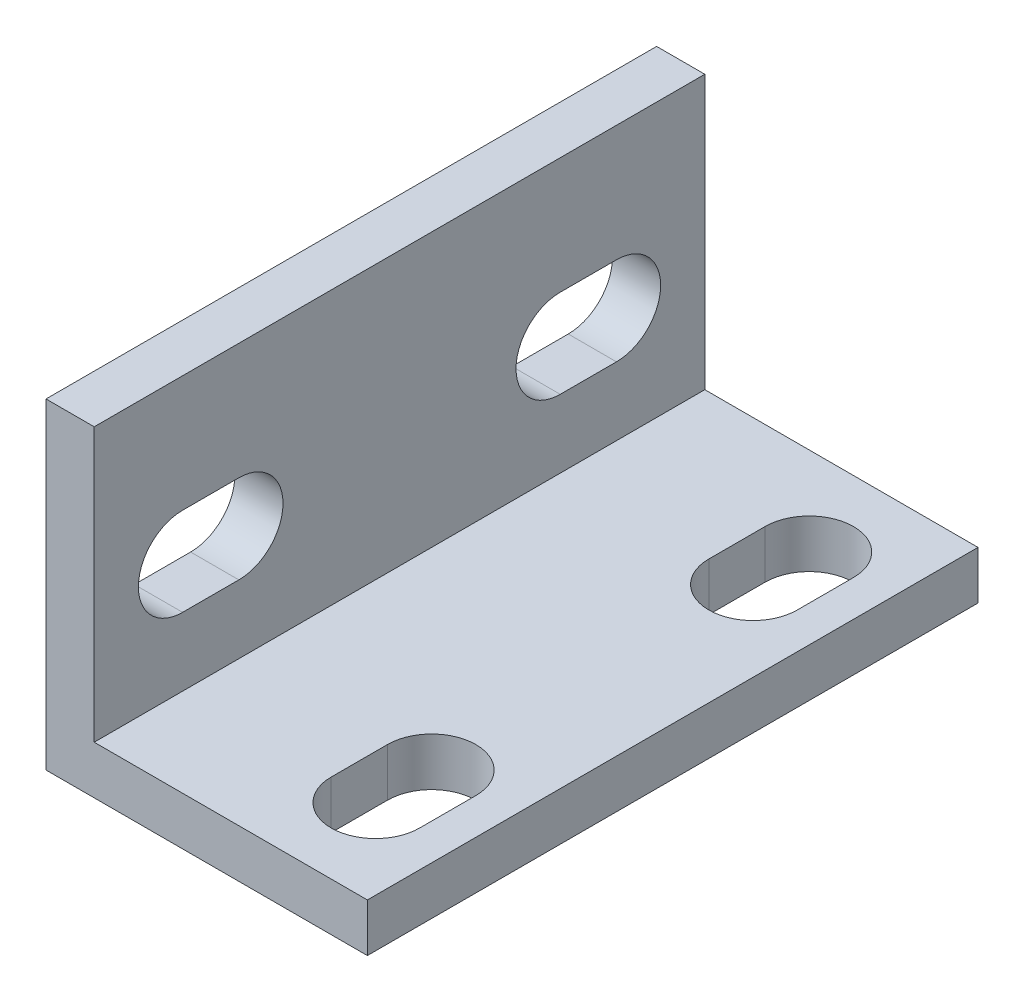
SolidWorks part; units mm, degrees
material "6061-T6 (SS)"
ref_plane "Front Plane" through (0, 0, 0) normal (0, 0, 1) x (1, 0, 0)
ref_plane "Top Plane" through (0, 0, 0) normal (0, 1, 0) x (1, 0, 0)
ref_plane "Right Plane" through (0, 0, 0) normal (1, 0, 0) x (0, 0, -1)
sketch "Sketch1" plane through (0, 0, 0) normal (0, 0, 1) x (1, 0, 0)
  line L0 (0, 20) -> (0, 0)
  line L1 (0, 0) -> (20, 0)
  dimension "D1" = 20
extrude "Extrude-Thin1" add sketch "Sketch1" along normal blind 38 thin thin type one direction reverse wall 3
sketch "Sketch2" plane through (3, 0, 0) normal (1, 0, 0) x (0, 0, -1)
  line L0 (-19, 20) -> (-19, 3) construction
  line L1 (-38, 20) -> (0, 20) construction
  line L2 (-38, 3) -> (0, 3) construction
  line L3 (-29, 10) -> (-32.5, 10) construction
  line L4 (-29, 7.25) -> (-32.5, 7.25)
  line L5 (-29, 12.75) -> (-32.5, 12.75)
  line L6 (-9, 10) -> (-5.5, 10) construction
  line L7 (-9, 7.25) -> (-5.5, 7.25)
  line L8 (-38, 3) -> (0, 3) construction
  line L9 (-9, 12.75) -> (-5.5, 12.75)
  arc A0 (-29, 7.25) -> (-29, 12.75) centre (-29, 10) ccw
  arc A1 (-32.5, 12.75) -> (-32.5, 7.25) centre (-32.5, 10) ccw
  arc A2 (-9, 7.25) -> (-9, 12.75) centre (-9, 10) cw
  arc A3 (-5.5, 12.75) -> (-5.5, 7.25) centre (-5.5, 10) cw
  point P8 (-30.75, 10)
  point P15 (-7.25, 10)
  dimension "D1" = 3.5
  dimension "D2" = 5.5
  dimension "D3" = 7
  dimension "D4" = 23.5
extrude "Cut-Extrude1" cut sketch "Sketch2" against normal through all
sketch "Sketch3" plane through (0, 3, 0) normal (0, 1, 0) x (1, 0, 0)
  line L0 (20, -19) -> (3, -19) construction
  line L1 (20, -38) -> (20, 0) construction
  line L2 (3, -38) -> (3, 0) construction
  line L3 (15, -32.5) -> (15, -29) construction
  line L4 (12.25, -32.5) -> (12.25, -29)
  line L5 (17.75, -32.5) -> (17.75, -29)
  line L6 (15, -5.5) -> (15, -9) construction
  line L7 (12.25, -5.5) -> (12.25, -9)
  line L8 (17.75, -5.5) -> (17.75, -9)
  arc A0 (12.25, -32.5) -> (17.75, -32.5) centre (15, -32.5) ccw
  arc A1 (17.75, -29) -> (12.25, -29) centre (15, -29) ccw
  arc A2 (12.25, -5.5) -> (17.75, -5.5) centre (15, -5.5) cw
  arc A3 (17.75, -9) -> (12.25, -9) centre (15, -9) cw
  point P8 (15, -30.75)
  point P15 (15, -7.25)
  dimension "D1" = 3.5
  dimension "D2" = 5.5
  dimension "D3" = 12
  dimension "D4" = 23.5
extrude "Cut-Extrude2" cut sketch "Sketch3" against normal through all
ref_plane "Plane1" through (0, 0, 19) normal (0, 0, 1) x (1, 0, 0)
ref_plane "Plane2" through (0, 0, 7.25) normal (0, 0, 1) x (1, 0, 0)
ref_plane "Plane3" through (0, 0, 30.75) normal (0, 0, 1) x (1, 0, 0)
ref_plane "Plane4" through (15, 0, 0) normal (1, 0, 0) x (0, 0, -1)
ref_plane "Plane5" through (0, 10, 0) normal (0, 1, 0) x (1, 0, 0)
